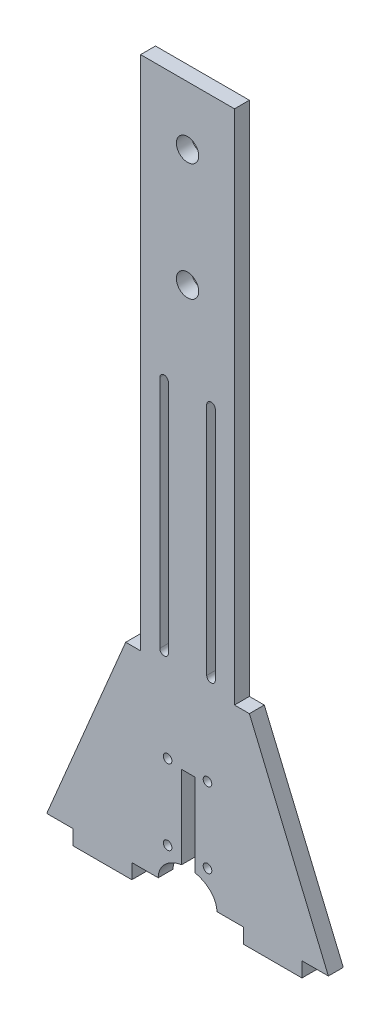
SolidWorks part; units mm, degrees
material "ABS"
ref_plane "Plan de face" through (0, 0, 0) normal (0, 0, 1) x (1, 0, 0)
ref_plane "Plan de dessus" through (0, 0, 0) normal (0, 1, 0) x (1, 0, 0)
ref_plane "Plan de droite" through (0, 0, 0) normal (1, 0, 0) x (0, 0, -1)
sketch "Esquisse1" plane through (0, 0, 0) normal (0, 0, 1) x (1, 0, 0)
  line L1 (-20, 300) -> (20, 300)
  line L2 (-20, 300) -> (-20, 80)
  line L4 (20, 300) -> (20, 80)
  line L8 (-60, 0) -> (60, 0)
  line L9 (26.35, 80) -> (-26.35, 80) construction
  line L10 (26.35, 80) -> (60, 0)
  line L11 (-26.35, 80) -> (-60, 0)
  line L12 (26.35, 80) -> (20, 80)
  line L13 (-20, 80) -> (-26.35, 80)
  point P1 (0, 0)
  point P2 (0, 300)
  point P8 (0, 80)
  dimension "D1" = 80
  dimension "D2" = 120
  dimension "D3" = 40
  dimension "D4" = 300
  dimension "D5" = 6.35
extrude "Boss.-Extru.1" add sketch "Esquisse1" along normal mid plane 6.35
sketch "Sketch1" plane through (0, 0, 3.175) normal (0, 0, 1) x (1, 0, 0)
  line L0 (20, 300) -> (-20, 300) construction
  circle A0 centre (0, 275) radius 4.7625
  circle A1 centre (0, 225) radius 4.7625
  point P6 (0, 300)
  dimension "D2" = 25
  dimension "D3" = 9.525
  dimension "D1" = 50
extrude "Cut-Extrude1" cut sketch "Sketch1" against normal up to surface (6.35 mm away) up to face at (0, 115, -3.175)
sketch "Esquisse2" plane through (0, 0, 3.175) normal (0, 0, 1) x (1, 0, 0)
  line L0 (-60, 0) -> (60, 0) construction
  line L1 (-12.5, 0) -> (12.5, 0)
  ellipse E0 centre (0, 0) end of major axis (12.5, 0) minor radius 10 (-12.5, 0) -> (12.5, 0) cw
  dimension "D1" = 10
  dimension "D2" = 25
extrude "Enlèv. mat.-Extru.1" cut sketch "Esquisse2" against normal up to surface (6.35 mm away) up to face at (-4.7625, 275, -3.175)
sketch "Esquisse3" plane through (0, 0, 3.175) normal (0, 0, 1) x (1, 0, 0)
  line L1 (-2.54, 45) -> (3.175, 45)
  line L2 (-2.54, 45) -> (-2.54, 0)
  line L3 (-2.54, 0) -> (3.175, 0)
  line L4 (3.175, 45) -> (3.175, 0)
  line L5 (-2.54, 43.6375) -> (-2.54, -57.9625) construction
  line L6 (3.175, -57.9625) -> (3.175, 43.6375) construction
  line L7 (-60, 0) -> (-12.5, 0) construction
  dimension "D1" = 0
  dimension "D2" = 45
extrude "Enlèv. mat.-Extru.2" cut sketch "Esquisse3" against normal up to surface (6.35 mm away) up to face at (0, 93, -3.175)
sketch "Esquisse5" plane through (0, 0, -3.175) normal (0, 0, -1) x (-1, 0, 0)
  line L0 (0, 3.4925) -> (0, -3.4925) construction
  line L2 (3.4925, 30) -> (-3.4925, 30) construction
  circle A0 centre (-8.5, 46) radius 1.83
  circle A1 centre (-8.5, 46) radius 1.83 construction
  circle A2 centre (8.5, 46) radius 1.83
  circle A3 centre (8.5, 14) radius 1.83
  circle A4 centre (-8.5, 14) radius 1.83
extrude "Enlèv. mat.-Extru.3" cut sketch "Esquisse5" against normal up to next
sketch "Esquisse6" plane through (0, 0, 3.175) normal (0, 0, 1) x (1, 0, 0)
  line L0 (-11.835, 185) -> (-11.835, 85)
  line L1 (-8.165, 185) -> (-8.165, 85)
  line L2 (20, 300) -> (-20, 300) construction
  line L3 (0, -3.4925) -> (0, 3.4925) construction
  line L4 (11.835, 185) -> (11.835, 85)
  line L5 (8.165, 185) -> (8.165, 85)
  circle A0 centre (-10, 101.5) radius 1.835 construction
  arc A1 (-8.165, 185) -> (-11.835, 185) centre (-10, 185) ccw
  arc A2 (-8.165, 85) -> (-11.835, 85) centre (-10, 85) cw
  arc A3 (8.165, 85) -> (11.835, 85) centre (10, 85) ccw
  arc A4 (8.165, 185) -> (11.835, 185) centre (10, 185) cw
  dimension "D1" = 100
  dimension "D2" = 115
extrude "Enlèv. mat.-Extru.4" cut sketch "Esquisse6" against normal up to next
sketch "Sketch3" plane through (0, 0, 0) normal (0, -1, 0) x (-1, 0, 0)
  line L0 (-12.5, 3.175) -> (-60, 3.175) construction
  line L1 (-48.75, 3.175) -> (-23.75, 3.175)
  line L2 (-48.75, 3.175) -> (-48.75, -3.175)
  line L3 (-48.75, -3.175) -> (-23.75, -3.175)
  line L4 (-23.75, 3.175) -> (-23.75, -3.175)
  line L5 (-12.5, -3.175) -> (-60, -3.175) construction
  line L6 (0, 3.4925) -> (0, -3.4925) construction
  line L7 (23.75, 3.175) -> (23.75, -3.175)
  line L8 (48.75, -3.175) -> (23.75, -3.175)
  line L9 (48.75, 3.175) -> (48.75, -3.175)
  line L10 (48.75, 3.175) -> (23.75, 3.175)
  point P8 (-36.25, 3.175)
  point P9 (-36.25, 3.175)
  dimension "D1" = 25
extrude "Boss-Extrude2" add sketch "Sketch3" along normal blind 6.35
